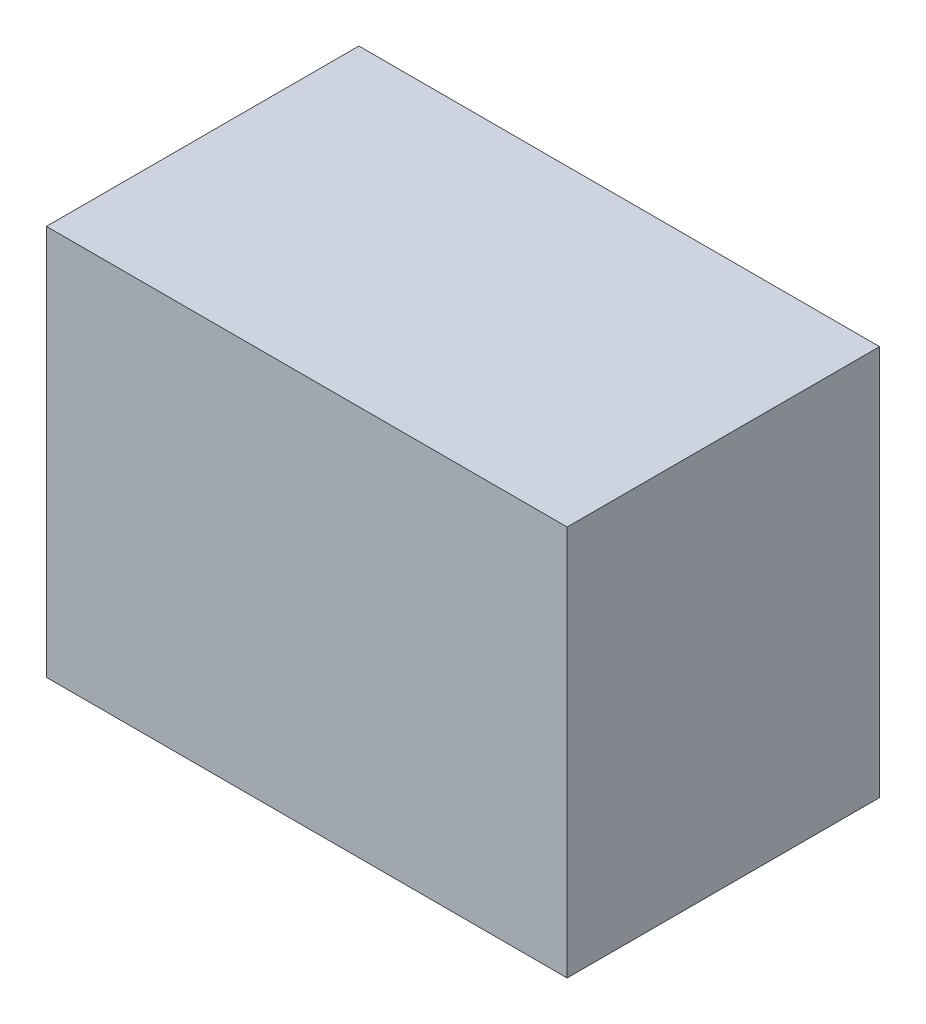
SolidWorks part; units mm, degrees
ref_plane "Front Plane" through (0, 0, 0) normal (0, 0, 1) x (1, 0, 0)
ref_plane "Top Plane" through (0, 0, 0) normal (0, 1, 0) x (1, 0, 0)
ref_plane "Right Plane" through (0, 0, 0) normal (1, 0, 0) x (0, 0, -1)
sketch "Esquisse1" plane through (0, 0, 0) normal (0, 0, 1) x (1, 0, 0)
  line L1 (0, 0) -> (20, 0)
  line L2 (0, 0) -> (0, 15)
  line L3 (0, 15) -> (20, 15)
  line L4 (20, 0) -> (20, 15)
  dimension "D1" = 20
  dimension "D2" = 15
extrude "Boss.-Extru.1" add sketch "Esquisse1" along normal blind 12
sketch "Esquisse2" plane through (0, 0, 0) normal (0, -1, 0) x (1, 0, 0)
  line L0 (0, 0) -> (20, 0) construction
  line L1 (1, 1) -> (19, 1)
  line L2 (1, 1) -> (1, 11)
  line L3 (1, 11) -> (19, 11)
  line L4 (19, 1) -> (19, 11)
  line L5 (20, 12) -> (20, 0) construction
  dimension "D1" = 10
  dimension "D2" = 1
  dimension "D3" = 1
  dimension "D4" = 18
extrude "Enlèv. mat.-Extru.1" cut sketch "Esquisse2" against normal blind 12
